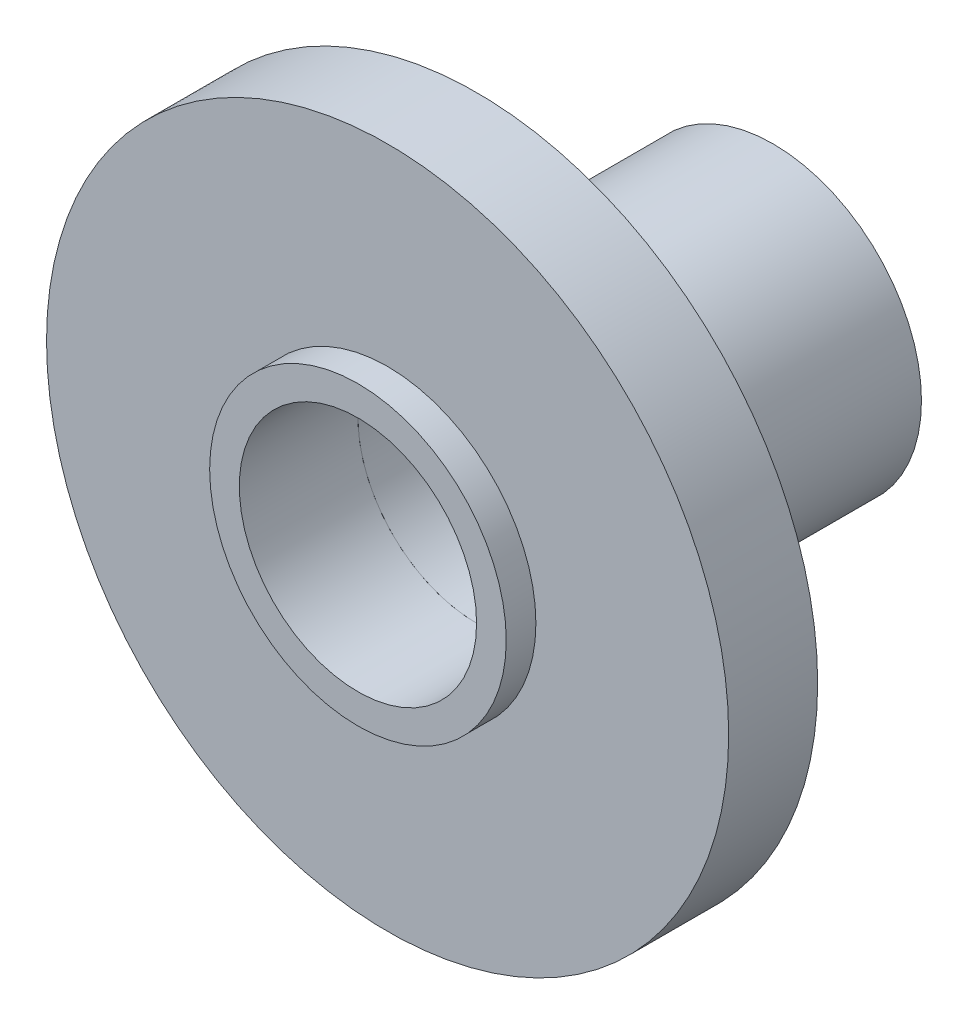
SolidWorks part; units mm, degrees
ref_plane "Front Plane" through (0, 0, 0) normal (0, 0, 1) x (1, 0, 0)
ref_plane "Top Plane" through (0, 0, 0) normal (0, 1, 0) x (1, 0, 0)
ref_plane "Right Plane" through (0, 0, 0) normal (1, 0, 0) x (0, 0, -1)
sketch "Sketch1" plane through (0, 0, 0) normal (0, 0, 1) x (1, 0, 0)
  circle A0 centre (0, 0) radius 5
  circle A1 centre (0, 0) radius 4
  dimension "D1" = 10
  dimension "D2" = 8
extrude "Boss-Extrude1" add sketch "Sketch1" along normal blind 1
sketch "Sketch2" plane through (0, 0, 0) normal (0, 0, 1) x (1, 0, 0)
  circle A0 centre (0, 0) radius 11.5
  circle A1 centre (0, 0) radius 4
  dimension "D1" = 23
  dimension "D2" = 8
extrude "Boss-Extrude2" add sketch "Sketch2" against normal blind 3
sketch "Sketch5" plane through (0, 0, -3) normal (0, 0, -1) x (-1, 0, 0)
  circle A0 centre (0, 0) radius 5
  circle A1 centre (0, 0) radius 4
extrude "Boss-Extrude3" add sketch "Sketch5" along normal blind 10 separate body
